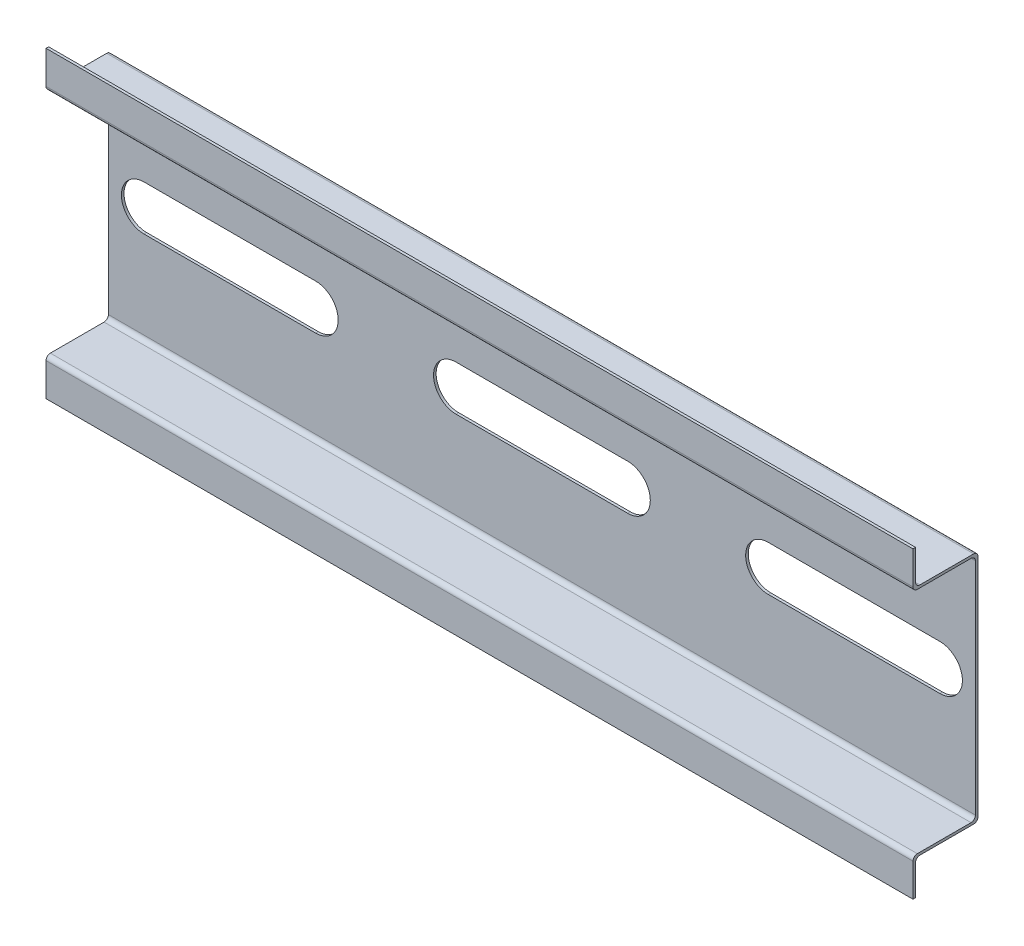
SolidWorks part; units mm, degrees
material "AISI 304"
ref_plane "Ebene vorne" through (0, 0, 0) normal (0, 0, 1) x (1, 0, 0)
ref_plane "Ebene oben" through (0, 0, 0) normal (0, 1, 0) x (1, 0, 0)
ref_plane "Ebene rechts" through (0, 0, 0) normal (1, 0, 0) x (0, 0, -1)
sketch "Skizze1" plane through (0, 0, 0) normal (1, 0, 0) x (0, 0, -1)
  line L0 (-3.75, 17.5) -> (-3.75, 13.7)
  line L1 (3.75, -17.5) -> (-3.75, -17.5) construction
  line L2 (3.75, -17.5) -> (3.75, 17.5) construction
  line L3 (3.75, 17.5) -> (-3.75, 17.5) construction
  line L4 (-3.75, -17.5) -> (-3.75, 17.5) construction
  line L5 (0, 17.5) -> (0, -17.5) construction
  line L6 (3.75, 0) -> (-3.75, 0) construction
  line L7 (-3.25, 13.2) -> (2.95, 13.2)
  line L8 (3.45, 12.7) -> (3.45, -12.7)
  line L9 (2.95, -13.2) -> (-3.25, -13.2)
  line L10 (-3.75, -13.7) -> (-3.75, -17.5)
  line L11 (-3.75, -17.5) -> (-3.45, -17.5)
  line L12 (-3.45, -17.5) -> (-3.45, -14)
  line L13 (-2.95, -13.5) -> (3.25, -13.5)
  line L14 (3.75, -13) -> (3.75, 13)
  line L15 (3.25, 13.5) -> (-2.95, 13.5)
  line L16 (-3.45, 14) -> (-3.45, 17.5)
  line L17 (-3.45, 17.5) -> (-3.75, 17.5)
  arc A0 (-3.25, -13.2) -> (-3.75, -13.7) centre (-3.25, -13.7) ccw
  arc A1 (-3.45, -14) -> (-2.95, -13.5) centre (-2.95, -14) cw
  arc A2 (3.45, -12.7) -> (2.95, -13.2) centre (2.95, -12.7) cw
  arc A3 (3.25, -13.5) -> (3.75, -13) centre (3.25, -13) ccw
  arc A4 (-3.75, 13.7) -> (-3.25, 13.2) centre (-3.25, 13.7) ccw
  arc A5 (-2.95, 13.5) -> (-3.45, 14) centre (-2.95, 14) cw
  arc A6 (2.95, 13.2) -> (3.45, 12.7) centre (2.95, 12.7) cw
  arc A7 (3.75, 13) -> (3.25, 13.5) centre (3.25, 13) ccw
  point P0 (0, 0)
  point P17 (-3.75, -13.2)
  point P24 (3.75, -13.5)
  point P27 (-3.75, 13.2)
  point P40 (3.75, 13.5)
  dimension "D4" = 0.5
  dimension "D1" = 7.5
  dimension "D2" = 35
  dimension "D3" = 0.3
  dimension "D5" = 0.3
  dimension "D6" = 27
extrude "Aufsatz-Linear austragen1" add sketch "Skizze1" along normal blind 100
sketch "Skizze2" plane through (0, 0, -3.75) normal (0, 0, -1) x (-1, 0, 0)
  line L0 (-100, 0) -> (0, 0) construction
  line L1 (-100, -13) -> (-100, 13) construction
  line L2 (-95.9, 0) -> (-76.1, 0) construction
  line L3 (-95.9, 2.6) -> (-76.1, 2.6)
  line L4 (-95.9, -2.6) -> (-76.1, -2.6)
  line L5 (-59.9, 0) -> (-40.1, 0) construction
  line L6 (-59.9, 2.6) -> (-40.1, 2.6)
  line L7 (-59.9, -2.6) -> (-40.1, -2.6)
  line L8 (-23.9, 0) -> (-4.1, 0) construction
  line L9 (-23.9, 2.6) -> (-4.1, 2.6)
  line L10 (-23.9, -2.6) -> (-4.1, -2.6)
  arc A0 (-95.9, 2.6) -> (-95.9, -2.6) centre (-95.9, 0) ccw
  arc A1 (-76.1, -2.6) -> (-76.1, 2.6) centre (-76.1, 0) ccw
  arc A2 (-59.9, 2.6) -> (-59.9, -2.6) centre (-59.9, 0) ccw
  arc A3 (-40.1, -2.6) -> (-40.1, 2.6) centre (-40.1, 0) ccw
  arc A4 (-23.9, 2.6) -> (-23.9, -2.6) centre (-23.9, 0) ccw
  arc A5 (-4.1, -2.6) -> (-4.1, 2.6) centre (-4.1, 0) ccw
  point P7 (-86, 0)
  point P12 (0, 0)
  point P13 (-90.4817, 0)
  point P16 (-50, 0)
  point P23 (-14, 0)
  dimension "D2" = 19.8
  dimension "D1" = 5.2
  dimension "D4" = 36
  dimension "D3" = 3
extrude "Schnitt-Linear austragen1" cut sketch "Skizze2" against normal through all
